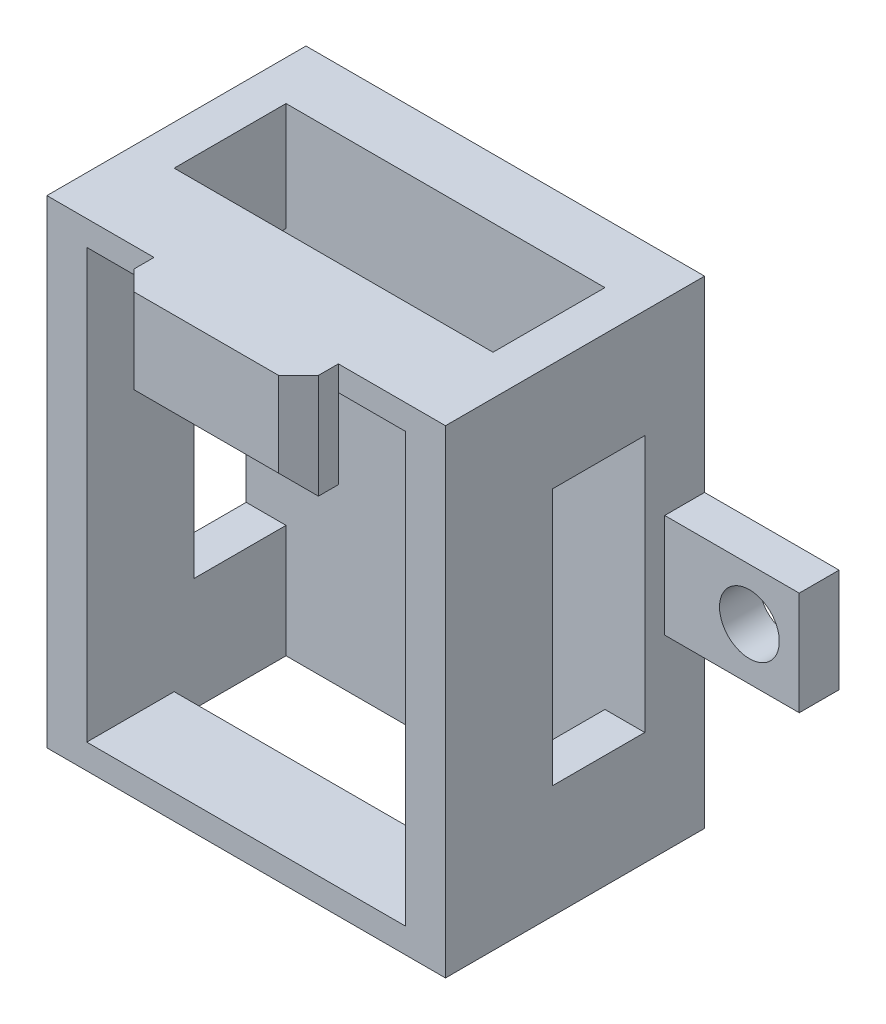
SolidWorks part; units mm, degrees
ref_plane "Front" through (0, 0, 0) normal (0, 0, 1) x (1, 0, 0)
ref_plane "Top" through (0, 0, 0) normal (0, 1, 0) x (1, 0, 0)
ref_plane "Right" through (0, 0, 0) normal (1, 0, 0) x (0, 0, -1)
sketch "Sketch1" plane through (0, 0, 0) normal (0, 0, 1) x (1, 0, 0)
  line L1 (-10, 12) -> (10, 12)
  line L2 (-10, 12) -> (-10, -12)
  line L3 (-10, -12) -> (10, -12)
  line L4 (10, 12) -> (10, -12)
  line L5 (-10, 12) -> (10, -12) construction
  line L6 (-10, -12) -> (10, 12) construction
  point P0 (0, 0)
  dimension "D1" = 24
  dimension "D2" = 20
extrude "Boss-Extrude1" add sketch "Sketch1" along normal blind 3
sketch "Sketch2" plane through (0, 0, 3) normal (0, 0, 1) x (1, 0, 0)
  line L1 (-8, -10.75) -> (8, -10.75)
  line L2 (-8, -10.75) -> (-8, 10.75)
  line L3 (-8, 10.75) -> (8, 10.75)
  line L4 (8, -10.75) -> (8, 10.75)
  line L5 (-8, -10.75) -> (8, 10.75) construction
  line L6 (-8, 10.75) -> (8, -10.75) construction
  line L7 (-10, 12) -> (10, 12)
  line L8 (-10, 12) -> (-10, -12)
  line L9 (-10, -12) -> (10, -12)
  line L10 (10, 12) -> (10, -12)
  line L11 (-10, 12) -> (10, -12) construction
  line L12 (-10, -12) -> (10, 12) construction
  point P0 (0, 0)
  point P6 (0, 0)
  dimension "D1" = 21.5
  dimension "D2" = 16
extrude "Boss-Extrude2" add sketch "Sketch2" along normal blind 10
sketch "Sketch3" plane through (0, 0, 13) normal (0, 0, 1) x (1, 0, 0)
  line L0 (10, 12) -> (-10, 12) construction
  line L1 (-4.625, 12) -> (4.625, 12)
  line L2 (-4.625, 12) -> (-4.625, 6.75)
  line L3 (-4.625, 6.75) -> (4.625, 6.75)
  line L4 (4.625, 12) -> (4.625, 6.75)
  line L5 (0, -7.15) -> (0, 7.15) construction
  line L6 (8, 10.75) -> (-8, 10.75) construction
  point P6 (0, 12)
  dimension "D1" = 4
  dimension "D2" = 9.25
extrude "Boss-Extrude3" add sketch "Sketch3" along normal blind 2
chamfer "Chamfer1" distance 1 angle 45 3 edges at (4.625, 9.375, 15) (-4.625, 9.375, 15) (0, 6.75, 15)
sketch "Sketch4" plane through (0, 0, 0) normal (0, 0, -1) x (-1, 0, 0)
  line L0 (-10, -12) -> (-10, 12) construction
  line L1 (-10, 2.6) -> (-16.75, 2.6)
  line L2 (-10, 2.6) -> (-10, -2.6)
  line L3 (-10, -2.6) -> (-16.75, -2.6)
  line L4 (-16.75, 2.6) -> (-16.75, -2.6)
  line L6 (-10, -12) -> (-10, 12)
  line L7 (0, 7.15) -> (0, -7.15) construction
  line L8 (10, -12) -> (10, 12)
  line L9 (16.75, 2.6) -> (16.75, -2.6)
  line L10 (10, -2.6) -> (16.75, -2.6)
  line L11 (10, 2.6) -> (10, -2.6)
  line L12 (10, 2.6) -> (16.75, 2.6)
  circle A0 centre (-14.25, 0) radius 1.5
  circle A1 centre (14.25, 0) radius 1.5
  point P8 (-16.75, 0)
  point P9 (-10, 0)
  line M6 (-10, 12) -> (-10, -12)
  dimension "D1" = 3
  dimension "D3" = 28.5
  dimension "D2" = 5.2
  dimension "D4" = 6.75
extrude "Boss-Extrude4" add sketch "Sketch4" against normal blind 2 contours L1 L4 L3 A0 M6 | L12 L8 L10 L9 A1
sketch "Sketch5" plane through (0, 12, 0) normal (0, 1, 0) x (1, 0, 0)
  line L1 (-8, -3) -> (8, -3)
  line L2 (-8, -3) -> (-8, -8.6159)
  line L3 (-8, -8.6159) -> (8, -8.6159)
  line L4 (8, -3) -> (-8, -3)
  line L5 (-8, -3) -> (-8, -13)
  line L6 (-8, -13) -> (8, -13)
  line L7 (8, -13) -> (8, -3)
  line L8 (8, -3) -> (-8, -3)
  line L9 (-8, -3) -> (-8, -8.6159)
  line L11 (8, -8.6159) -> (8, -3)
  line L12 (8, -3) -> (8, -8.6159)
  dimension "D1" = 0
extrude "Cut-Extrude1" cut sketch "Sketch5" against normal through all contours L2 L1 L12 L3
sketch "Sketch6" plane through (-10, 0, 0) normal (-1, 0, 0) x (0, 0, 1)
  line L1 (3, 6.5698) -> (7.62, 6.5698)
  line L2 (3, 6.5698) -> (3, -6.3298)
  line L3 (3, -6.3298) -> (7.62, -6.3298)
  line L4 (7.62, 6.5698) -> (7.62, -6.3298)
  line L8 (13, 10.75) -> (8.6159, 10.75)
  line L9 (8.6159, 10.75) -> (8.6159, 12)
  line L10 (8.6159, 12) -> (3, 12)
  line L11 (3, 12) -> (3, -12)
  line L12 (3, -12) -> (8.6159, -12)
  line L13 (8.6159, -12) -> (8.6159, -10.75)
  line L14 (8.6159, -10.75) -> (13, -10.75)
  line L15 (13, -10.75) -> (13, 10.75)
  line L16 (13, 10.75) -> (8.6159, 10.75)
  line L17 (8.6159, 10.75) -> (8.6159, 12)
  line L18 (8.6159, 12) -> (3, 12)
  line L19 (3, 6.5698) -> (3, -6.3298)
  line L20 (3, -12) -> (8.6159, -12)
  line L21 (8.6159, -12) -> (8.6159, -10.75)
  line L22 (8.6159, -10.75) -> (13, -10.75)
  line L23 (13, -10.75) -> (13, 10.75)
  dimension "D1" = 0
extrude "Cut-Extrude4" cut sketch "Sketch6" against normal through all contours L4 L1 L2 L3
